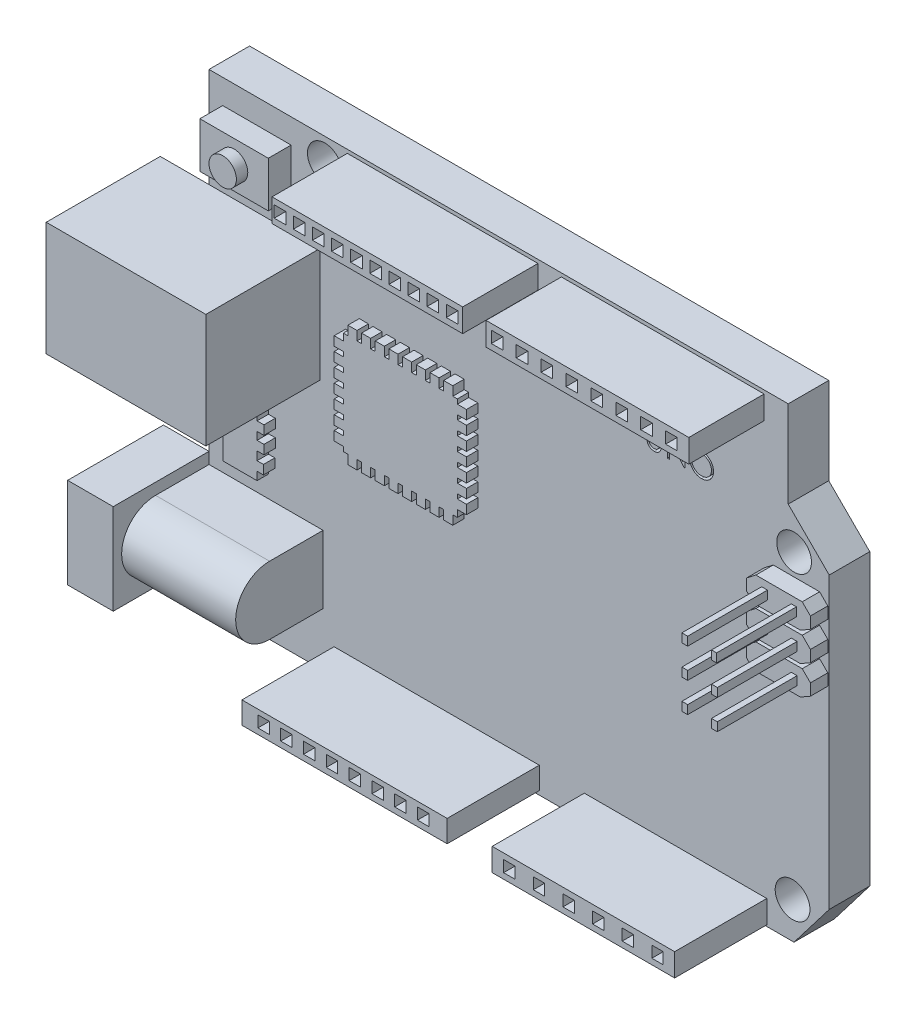
SolidWorks part; units mm, degrees
ref_plane "Front Plane" through (0, 0, 0) normal (0, 0, 1) x (1, 0, 0)
ref_plane "Top Plane" through (0, 0, 0) normal (0, 1, 0) x (1, 0, 0)
ref_plane "Right Plane" through (0, 0, 0) normal (1, 0, 0) x (0, 0, -1)
sketch "Sketch1" plane through (0, 0, 0) normal (0, 0, 1) x (1, 0, 0)
  line L0 (-21.0015, 8.0601) -> (-21.0015, -12.2599)
  line L1 (4.6525, -12.2599) -> (6.197, -10.2435)
  line L2 (6.197, -10.2435) -> (6.197, 2.4565)
  line L4 (4.3985, 8.0601) -> (-21.0015, 8.0601)
  line L5 (-21.0015, -12.2599) -> (4.6525, -12.2599)
  line L6 (6.197, 2.4565) -> (4.3985, 4.2501)
  line L7 (4.3985, 4.2501) -> (4.3985, 8.0601)
  dimension "D1" = 25.654
  dimension "D2" = 20.32
  dimension "D3" = 25.4
  dimension "D4" = 3.81
  dimension "D5" = 2.54
  dimension "D6" = 2.54
  dimension "D7" = 12.7
  dimension "D8" = 27.1985
  dimension "D9" = 20.32
extrude "Boss-Extrude1" add sketch "Sketch1" along normal blind 1.778
sketch "Sketch2" plane through (0, 0, 0) normal (0, 0, 1) x (1, 0, 0)
  line L0 (4.3985, 8.0601) -> (-21.0015, 8.0601) construction
  line L1 (-21.0015, -12.2599) -> (4.6525, -12.2599) construction
  line L2 (-21.0015, 8.0601) -> (-21.0015, -12.2599) construction
  line L3 (6.197, 2.4565) -> (4.3985, 4.2501) construction
  line L4 (4.6525, -12.2599) -> (6.197, -10.2435) construction
  circle A0 centre (4.6572, 2.5572) radius 0.762
  circle A1 centre (-15.9215, 7.0441) radius 0.762
  circle A2 centre (-18.4615, -11.2439) radius 0.762
  circle A3 centre (4.589, -10.6719) radius 0.762
  dimension "D1" = 1.524
  dimension "D2" = 1.524
  dimension "D3" = 1.524
  dimension "D4" = 1.524
  dimension "D10" = 1.016
  dimension "D11" = 1.016
  dimension "D6" = 1.016
  dimension "D7" = 1.016
  dimension "D8" = 5.08
  dimension "D9" = 2.54
extrude "Cut-Extrude6" cut sketch "Sketch2" against normal blind 7.874 and the other way blind 6.35
sketch "Sketch7" plane through (0, 0, 0) normal (0, 0, 1) x (1, 0, 0)
  line L0 (3.8952, 2.5572) -> (3.8952, -2.4896) construction
  line L1 (5.4192, 2.5572) -> (5.4192, -2.4896) construction
  line L2 (5.4192, 2.5572) -> (5.6732, 2.5572) construction
  line L3 (3.8952, 2.5572) -> (3.6412, 2.5572) construction
  line L4 (3.743, 1.6105) -> (5.775, 1.6105)
  line L5 (5.775, 1.6105) -> (6.1342, 1.2512)
  line L6 (6.1342, 1.2512) -> (6.1342, 0.7432)
  line L7 (6.1342, 0.7432) -> (5.6928, 0.4919)
  line L8 (5.6928, 0.4919) -> (3.6412, 0.4919)
  line L9 (3.6412, 0.4919) -> (3.3402, 0.7929)
  line L10 (3.3402, 0.7929) -> (3.3402, 1.3009)
  line L11 (3.3402, 1.3009) -> (3.743, 1.6105)
  line L12 (6.1342, 1.2512) -> (6.1342, -2.4896) construction
  line L13 (6.197, -10.2435) -> (6.197, 2.4565) construction
  line L14 (3.3402, 0.0309) -> (3.743, 0.3405)
  line L15 (3.743, 0.3405) -> (5.775, 0.3405)
  line L16 (5.775, 0.3405) -> (6.1342, -0.0188)
  line L17 (6.1342, -0.0188) -> (6.1342, -0.5268)
  line L18 (6.1342, -0.5268) -> (5.6928, -0.7781)
  line L19 (5.6928, -0.7781) -> (3.6412, -0.7781)
  line L20 (3.6412, -0.7781) -> (3.3402, -0.4771)
  line L21 (3.3402, -0.4771) -> (3.3402, 0.0309)
  line L22 (3.3402, -1.2391) -> (3.743, -0.9295)
  line L23 (3.743, -0.9295) -> (5.775, -0.9295)
  line L24 (5.775, -0.9295) -> (6.1342, -1.2888)
  line L25 (6.1342, -1.2888) -> (6.1342, -1.7968)
  line L26 (6.1342, -1.7968) -> (5.6928, -2.0481)
  line L27 (5.6928, -2.0481) -> (3.6412, -2.0481)
  line L28 (3.6412, -2.0481) -> (3.3402, -1.7471)
  line L29 (3.3402, -1.7471) -> (3.3402, -1.2391)
  circle A0 centre (4.6572, 2.5572) radius 0.762 construction
  dimension "D1" = 0.254
  dimension "D2" = 0.254
  dimension "D3" = 0.508
  dimension "D4" = 0.508
  dimension "D5" = 0.4257
  dimension "D6" = 0.508
  dimension "D7" = 0.508
  dimension "D8" = 0.508
  dimension "D9" = 0.0628
  dimension "D11" = 1.1185
  dimension "D10" = 3
extrude "Boss-Extrude5" add sketch "Sketch7" along normal blind 2.54
sketch "Sketch8" plane through (0, 0, 0) normal (0, 0, 1) x (1, 0, 0)
  line L0 (1.2329, 7.6506) -> (1.2329, 7.1426)
  line L1 (3.3411, 7.9046) -> (-5.5489, 7.9046)
  line L2 (3.3411, 7.9046) -> (3.3411, 6.8886)
  line L3 (3.3411, 6.8886) -> (-5.5489, 6.8886)
  line L4 (-5.5489, 7.9046) -> (-5.5489, 6.8886)
  line L5 (2.3251, 7.6506) -> (2.8331, 7.6506)
  line L6 (2.3251, 7.6506) -> (2.3251, 7.1426)
  line L7 (2.3251, 7.1426) -> (2.8331, 7.1426)
  line L8 (2.8331, 7.6506) -> (2.8331, 7.1426)
  line L9 (1.2329, 7.6506) -> (1.7409, 7.6506)
  line L10 (1.7409, 7.6506) -> (1.7409, 7.1426)
  line L11 (1.2329, 7.1426) -> (1.7409, 7.1426)
  line L12 (0.1407, 7.6506) -> (0.1407, 7.1426)
  line L13 (0.1407, 7.6506) -> (0.6487, 7.6506)
  line L14 (0.6487, 7.6506) -> (0.6487, 7.1426)
  line L15 (0.1407, 7.1426) -> (0.6487, 7.1426)
  line L16 (-0.9515, 7.6506) -> (-0.9515, 7.1426)
  line L17 (-0.9515, 7.6506) -> (-0.4435, 7.6506)
  line L18 (-0.4435, 7.6506) -> (-0.4435, 7.1426)
  line L19 (-0.9515, 7.1426) -> (-0.4435, 7.1426)
  line L20 (-2.0437, 7.6506) -> (-2.0437, 7.1426)
  line L21 (-2.0437, 7.6506) -> (-1.5357, 7.6506)
  line L22 (-1.5357, 7.6506) -> (-1.5357, 7.1426)
  line L23 (-2.0437, 7.1426) -> (-1.5357, 7.1426)
  line L24 (-3.1359, 7.6506) -> (-3.1359, 7.1426)
  line L25 (-3.1359, 7.6506) -> (-2.6279, 7.6506)
  line L26 (-2.6279, 7.6506) -> (-2.6279, 7.1426)
  line L27 (-3.1359, 7.1426) -> (-2.6279, 7.1426)
  line L28 (-4.2281, 7.6506) -> (-4.2281, 7.1426)
  line L29 (-4.2281, 7.6506) -> (-3.7201, 7.6506)
  line L30 (-3.7201, 7.6506) -> (-3.7201, 7.1426)
  line L31 (-4.2281, 7.1426) -> (-3.7201, 7.1426)
  line L32 (-5.3203, 7.6506) -> (-5.3203, 7.1426)
  line L33 (-5.3203, 7.6506) -> (-4.8123, 7.6506)
  line L34 (-4.8123, 7.6506) -> (-4.8123, 7.1426)
  line L35 (-5.3203, 7.1426) -> (-4.8123, 7.1426)
  line L36 (-8.1339, 7.6506) -> (-8.1339, 7.1426)
  line L37 (-6.5746, 7.9046) -> (-14.9348, 7.9046)
  line L38 (-6.5746, 7.9046) -> (-6.5746, 6.8886)
  line L39 (-6.5746, 6.8886) -> (-14.9348, 6.8886)
  line L40 (-14.9348, 7.9046) -> (-14.9348, 6.8886)
  line L41 (-7.2957, 7.6506) -> (-6.7877, 7.6506)
  line L42 (-7.2957, 7.6506) -> (-7.2957, 7.1426)
  line L43 (-7.2957, 7.1426) -> (-6.7877, 7.1426)
  line L44 (-6.7877, 7.6506) -> (-6.7877, 7.1426)
  line L45 (-8.1339, 7.6506) -> (-7.6259, 7.6506)
  line L46 (-7.6259, 7.6506) -> (-7.6259, 7.1426)
  line L47 (-8.1339, 7.1426) -> (-7.6259, 7.1426)
  line L48 (-8.9721, 7.6506) -> (-8.9721, 7.1426)
  line L49 (-8.9721, 7.6506) -> (-8.4641, 7.6506)
  line L50 (-8.4641, 7.6506) -> (-8.4641, 7.1426)
  line L51 (-8.9721, 7.1426) -> (-8.4641, 7.1426)
  line L52 (-9.8103, 7.6506) -> (-9.8103, 7.1426)
  line L53 (-9.8103, 7.6506) -> (-9.3023, 7.6506)
  line L54 (-9.3023, 7.6506) -> (-9.3023, 7.1426)
  line L55 (-9.8103, 7.1426) -> (-9.3023, 7.1426)
  line L56 (-10.6485, 7.6506) -> (-10.6485, 7.1426)
  line L57 (-10.6485, 7.6506) -> (-10.1405, 7.6506)
  line L58 (-10.1405, 7.6506) -> (-10.1405, 7.1426)
  line L59 (-10.6485, 7.1426) -> (-10.1405, 7.1426)
  line L60 (-11.4867, 7.6506) -> (-11.4867, 7.1426)
  line L61 (-11.4867, 7.6506) -> (-10.9787, 7.6506)
  line L62 (-10.9787, 7.6506) -> (-10.9787, 7.1426)
  line L63 (-11.4867, 7.1426) -> (-10.9787, 7.1426)
  line L64 (-12.3249, 7.6506) -> (-12.3249, 7.1426)
  line L65 (-12.3249, 7.6506) -> (-11.8169, 7.6506)
  line L66 (-11.8169, 7.6506) -> (-11.8169, 7.1426)
  line L67 (-12.3249, 7.1426) -> (-11.8169, 7.1426)
  line L68 (-13.1631, 7.6506) -> (-13.1631, 7.1426)
  line L69 (-13.1631, 7.6506) -> (-12.6551, 7.6506)
  line L70 (-12.6551, 7.6506) -> (-12.6551, 7.1426)
  line L71 (-13.1631, 7.1426) -> (-12.6551, 7.1426)
  line L72 (-14.0013, 7.6506) -> (-14.0013, 7.1426)
  line L73 (-14.0013, 7.6506) -> (-13.4933, 7.6506)
  line L74 (-13.4933, 7.6506) -> (-13.4933, 7.1426)
  line L75 (-14.0013, 7.1426) -> (-13.4933, 7.1426)
  line L76 (-14.8395, 7.6506) -> (-14.8395, 7.1426)
  line L77 (-14.8395, 7.6506) -> (-14.3315, 7.6506)
  line L78 (-14.3315, 7.6506) -> (-14.3315, 7.1426)
  line L79 (-14.8395, 7.1426) -> (-14.3315, 7.1426)
  point P4 (3.3411, 7.3966)
  point P9 (2.8331, 7.3966)
  point P46 (-6.7877, 7.3966)
  dimension "D1" = 8.89
  dimension "D2" = 1.016
  dimension "D3" = 0.508
  dimension "D4" = 0.508
  dimension "D5" = 0.508
  dimension "D6" = 7.874
  dimension "D8" = 0.508
  dimension "D9" = 0.508
  dimension "D10" = 0.508
  dimension "D12" = 0.5842
  dimension "D7" = 8
  dimension "D11" = 10
extrude "Boss-Extrude10" add sketch "Sketch8" along normal blind 5.08
sketch "Sketch9" plane through (0, 0, 2.54) normal (0, 0, 1) x (1, 0, 0)
  line L1 (3.997, 1.293) -> (4.251, 1.293)
  line L2 (3.997, 1.293) -> (3.997, 0.912)
  line L3 (3.997, 0.912) -> (4.251, 0.912)
  line L4 (4.251, 1.293) -> (4.251, 0.912)
  line L8 (5.267, 1.293) -> (5.267, 0.912)
  line L9 (5.267, 1.293) -> (5.521, 1.293)
  line L10 (5.521, 1.293) -> (5.521, 0.912)
  line L11 (5.267, 0.912) -> (5.521, 0.912)
  line L12 (5.297, 1.293) -> (5.297, 0.912)
  line L13 (5.297, 1.293) -> (5.551, 1.293)
  line L14 (5.551, 1.293) -> (5.551, 0.912)
  line L15 (5.297, 0.912) -> (5.551, 0.912)
  line L16 (5.297, -0.007) -> (5.297, -0.388)
  line L17 (5.297, -0.007) -> (5.551, -0.007)
  line L18 (5.551, -0.007) -> (5.551, -0.388)
  line L19 (5.297, -0.388) -> (5.551, -0.388)
  line L20 (5.297, -1.307) -> (5.297, -1.688)
  line L21 (5.297, -1.307) -> (5.551, -1.307)
  line L22 (5.551, -1.307) -> (5.551, -1.688)
  line L23 (5.297, -1.688) -> (5.551, -1.688)
  line L24 (3.997, -0.007) -> (3.997, -0.388)
  line L25 (3.997, -0.007) -> (4.251, -0.007)
  line L26 (4.251, -0.007) -> (4.251, -0.388)
  line L27 (3.997, -0.388) -> (4.251, -0.388)
  line L28 (3.997, -1.307) -> (3.997, -1.688)
  line L29 (3.997, -1.307) -> (4.251, -1.307)
  line L30 (4.251, -1.307) -> (4.251, -1.688)
  line L31 (3.997, -1.688) -> (4.251, -1.688)
  point P4 (3.997, 1.1025)
  dimension "D1" = 0.381
  dimension "D2" = 0.254
  dimension "D3" = 0.508
  dimension "D4" = 0.254
  dimension "D6" = 0.254
  dimension "D7" = 2
  dimension "D5" = 2
  dimension "D8" = 3
extrude "Boss-Extrude14" add sketch "Sketch9" along normal blind 3.5 contours L4 L1 L2 L3 | L9 L12 L11 L10 | L16 L19 L18 L17 | L24 L27 L26 L25 | L20 L23 L22 L21 | L28 L31 L30 L29
sketch "Sketch10" plane through (0, 0, 1.778) normal (0, 0, 1) x (1, 0, 0)
  line L1 (-20.4015, 6.9869) -> (-17.4015, 6.9869)
  line L2 (-20.4015, 6.9869) -> (-20.4015, 4.9869)
  line L3 (-20.4015, 4.9869) -> (-17.4015, 4.9869)
  line L4 (-17.4015, 6.9869) -> (-17.4015, 4.9869)
  dimension "D1" = 2
  dimension "D2" = 3
  dimension "D3" = 0.6
extrude "Boss-Extrude15" add sketch "Sketch10" along normal blind 1
sketch "Sketch11" plane through (0, 0, 2.778) normal (0, 0, 1) x (1, 0, 0)
  line L0 (-20.4015, 6.9869) -> (-20.4015, 4.9869) construction
  line L1 (-17.4015, 6.9869) -> (-20.4015, 6.9869) construction
  circle A0 centre (-18.9015, 5.9869) radius 0.6
  point P0 (-20.4015, 5.9869)
  point P1 (-18.9015, 6.9869)
  point P10 (-18.9015, 5.9869)
  dimension "D1" = 1.2
extrude "Boss-Extrude16" add sketch "Sketch11" along normal blind 0.5
sketch "Sketch21" plane through (0, 0, 1.778) normal (0, 0, 1) x (1, 0, 0)
  line L1 (-23.14, 3.687) -> (-16.14, 3.687)
  line L2 (-23.14, 3.687) -> (-23.14, -1.313)
  line L3 (-23.14, -1.313) -> (-16.14, -1.313)
  line L4 (-16.14, 3.687) -> (-16.14, -1.313)
  dimension "D1" = 7
  dimension "D2" = 5
extrude "Boss-Extrude20" add sketch "Sketch21" along normal blind 5 contours L2 L1 L4 L3
sketch "Sketch22" plane through (-23.14, 0, 0) normal (-1, 0, 0) x (0, 0, 1)
  line L0 (5.4441, 2.1094) -> (5.4441, 0.2551)
  line L1 (5.4441, 0.2551) -> (4.6306, -0.5583)
  line L2 (4.6306, -0.5583) -> (3.1119, -0.5583)
  line L3 (3.1119, -0.5583) -> (3.1119, 2.9417)
  line L4 (3.1119, 2.9417) -> (4.6119, 2.9417)
  line L5 (4.6119, 2.9417) -> (5.4441, 2.1094)
  line L6 (5.4441, 1.1823) -> (3.1119, 1.1917) construction
  line L7 (4.278, 1.187) -> (4.278, -0.5583) construction
  point P11 (4.278, 1.187)
  dimension "D1" = 45
  dimension "D2" = 45
  dimension "D3" = 1.5
  dimension "D4" = 3.5
  dimension "D5" = 2.5
  dimension "D6" = 2.5
extrude "Cut-Extrude9" cut sketch "Sketch22" against normal blind 6
sketch "Sketch23" plane through (-17.14, 0, 0) normal (-1, 0, 0) x (0, 0, 1)
  line L0 (4.8177, 1.1917) -> (3.906, 1.1917) construction
  line L1 (4.5825, 1.7725) -> (3.906, 1.7725)
  line L2 (4.5825, 1.7725) -> (4.5825, 0.6108)
  line L3 (4.5825, 0.6108) -> (3.906, 0.6108)
  line L4 (3.906, 1.7725) -> (3.906, 0.6108)
  line L5 (4.2443, 1.7725) -> (4.2443, 0.6108) construction
  line L6 (5.4441, 2.1094) -> (3.1119, 2.1094) construction
  line L7 (3.1119, 2.9417) -> (3.1119, -0.5583) construction
  point P5 (4.3619, 1.1917)
  dimension "D1" = 1.75
  dimension "D2" = 2.3322
  dimension "D3" = 1.25
  dimension "D4" = 1.1617
extrude "Boss-Extrude21" add sketch "Sketch23" along normal blind 6
sketch "Sketch25" plane through (0, 0, 1.778) normal (0, 0, 1) x (1, 0, 0)
  line L1 (-19.8949, -3.5053) -> (-18.3949, -3.5053)
  line L2 (-19.8949, -3.5053) -> (-19.8949, -6.0053)
  line L3 (-19.8949, -6.0053) -> (-18.3949, -6.0053)
  line L4 (-18.3949, -3.5053) -> (-18.3949, -3.7342)
  line L8 (-18.3949, -4.1342) -> (-18.3949, -4.4734)
  line L9 (-18.3949, -3.7342) -> (-18.0942, -3.7342)
  line L10 (-18.3949, -4.1342) -> (-18.0942, -4.1342)
  line L11 (-18.0942, -3.7342) -> (-18.0942, -4.1342)
  line L12 (-18.3949, -4.8734) -> (-18.3949, -5.2482)
  line L13 (-18.3949, -4.4734) -> (-18.0916, -4.4734)
  line L14 (-18.3949, -4.8734) -> (-18.0916, -4.8734)
  line L15 (-18.0916, -4.4734) -> (-18.0916, -4.8734)
  line L16 (-18.3949, -5.6482) -> (-18.3949, -6.0053)
  line L17 (-18.3949, -5.2482) -> (-18.1145, -5.2482)
  line L18 (-18.3949, -5.6482) -> (-18.1145, -5.6482)
  line L19 (-18.1145, -5.2482) -> (-18.1145, -5.6482)
  dimension "D1" = 2.5
  dimension "D2" = 1.5
  dimension "D3" = 0.3571
  dimension "D4" = 0.3748
  dimension "D6" = 0.4
  dimension "D7" = 0.4
  dimension "D8" = 0.4
extrude "Boss-Extrude22" add sketch "Sketch25" along normal blind 0.5
ref_plane "Plane2" through (0, 0, 0) normal (1, 0, 0) x (0, 0, -1)
sketch "Sketch30" plane through (0, 0, 0) normal (1, 0, 0) x (0, 0, -1)
  line L0 (-4.1243, -6.9435) -> (-1.6243, -6.9435)
  line L1 (-1.6243, -6.9435) -> (-1.6243, -9.9172)
  line L2 (-1.6243, -9.9172) -> (-4.1243, -9.9172)
  arc A0 (-4.1243, -9.9172) -> (-4.1243, -6.9435) centre (-4.1243, -8.4303) cw
  dimension "D1" = 2.5
extrude "Boss-Extrude25" add sketch "Sketch30" against normal blind 21 and the other way blind 1
sketch "Sketch31" plane through (1, 0, 0) normal (1, 0, 0) x (0, 0, -1)
  line L0 (-4.1243, -9.9172) -> (-1.778, -9.9172)
  line L1 (-1.778, -9.9172) -> (-1.778, -6.9435)
  line L2 (-1.778, -6.9435) -> (-4.1243, -6.9435)
  arc A0 (-4.1243, -9.9172) -> (-4.1243, -6.9435) centre (-4.1243, -8.4303) cw
  arc A1 (-4.1243, -6.9435) -> (-4.1243, -9.9172) centre (-4.1243, -8.4303) ccw construction
extrude "Cut-Extrude10" cut sketch "Sketch31" against normal blind 17
sketch "Sketch32" plane through (-21, 0, 0) normal (-1, 0, 0) x (0, 0, 1)
  line L1 (1.7793, -6.4435) -> (5.9793, -6.4435)
  line L2 (1.7793, -6.4435) -> (1.7793, -10.4172)
  line L3 (1.7793, -10.4172) -> (5.9793, -10.4172)
  line L4 (5.9793, -6.4435) -> (5.9793, -10.4172)
  dimension "D1" = 0.5
  dimension "D2" = 0.5
  dimension "D3" = 4.2
extrude "Boss-Extrude26" add sketch "Sketch32" along normal blind 2
sketch "Sketch33" plane through (-23, 0, 0) normal (-1, 0, 0) x (0, 0, 1)
  line L0 (5.9793, -8.4303) -> (1.7793, -8.4303) construction
  line L1 (5.9793, -10.4172) -> (5.9793, -6.4435) construction
  line L2 (1.7793, -6.4435) -> (1.7793, -10.4172) construction
  circle A0 centre (3.8793, -8.4303) radius 1.3
  point P6 (3.8793, -8.4303)
extrude "Cut-Extrude11" cut sketch "Sketch33" against normal blind 2
sketch "Sketch35" plane through (-23, 0, 0) normal (-1, 0, 0) x (0, 0, 1)
  line L0 (5.9793, -8.4303) -> (1.7793, -8.4303) construction
  line L1 (5.9793, -10.4172) -> (5.9793, -6.4435) construction
  line L2 (1.7793, -6.4435) -> (1.7793, -10.4172) construction
  circle A0 centre (3.8793, -8.4303) radius 0.2
  point P6 (3.8793, -8.4303)
  dimension "D1" = 0.4
extrude "Boss-Extrude27" add sketch "Sketch35" along normal blind 0.04 and the other way blind 2 contours A0
sketch "Sketch36" plane through (0, 0, 1.778) normal (0, 0, 1) x (1, 0, 0)
  line L0 (1.1581, -11.4468) -> (1.1581, -11.9468)
  line L1 (3.4581, -12.1968) -> (-4.5419, -12.1968)
  line L2 (3.4581, -12.1968) -> (3.4581, -11.1968)
  line L3 (3.4581, -11.1968) -> (-4.5419, -11.1968)
  line L4 (-4.5419, -12.1968) -> (-4.5419, -11.1968)
  line L5 (2.4581, -11.4468) -> (2.9581, -11.4468)
  line L6 (2.4581, -11.4468) -> (2.4581, -11.9468)
  line L7 (2.4581, -11.9468) -> (2.9581, -11.9468)
  line L8 (2.9581, -11.4468) -> (2.9581, -11.9468)
  line L9 (1.1581, -11.4468) -> (1.6581, -11.4468)
  line L10 (1.6581, -11.4468) -> (1.6581, -11.9468)
  line L11 (1.1581, -11.9468) -> (1.6581, -11.9468)
  line L12 (-0.1419, -11.4468) -> (-0.1419, -11.9468)
  line L13 (-0.1419, -11.4468) -> (0.3581, -11.4468)
  line L14 (0.3581, -11.4468) -> (0.3581, -11.9468)
  line L15 (-0.1419, -11.9468) -> (0.3581, -11.9468)
  line L16 (-1.4419, -11.4468) -> (-1.4419, -11.9468)
  line L17 (-1.4419, -11.4468) -> (-0.9419, -11.4468)
  line L18 (-0.9419, -11.4468) -> (-0.9419, -11.9468)
  line L19 (-1.4419, -11.9468) -> (-0.9419, -11.9468)
  line L20 (-2.7419, -11.4468) -> (-2.7419, -11.9468)
  line L21 (-2.7419, -11.4468) -> (-2.2419, -11.4468)
  line L22 (-2.2419, -11.4468) -> (-2.2419, -11.9468)
  line L23 (-2.7419, -11.9468) -> (-2.2419, -11.9468)
  line L24 (-4.0419, -11.4468) -> (-4.0419, -11.9468)
  line L25 (-4.0419, -11.4468) -> (-3.5419, -11.4468)
  line L26 (-3.5419, -11.4468) -> (-3.5419, -11.9468)
  line L27 (-4.0419, -11.9468) -> (-3.5419, -11.9468)
  point P8 (2.9581, -11.6968)
  dimension "D1" = 1
  dimension "D2" = 8
  dimension "D3" = 0.5
  dimension "D4" = 0.5
  dimension "D5" = 0.5
  dimension "D6" = 0.5
extrude "Boss-Extrude28" add sketch "Sketch36" along normal blind 4.04
sketch "Sketch39" plane through (0, 0, 1.778) normal (0, 0, 1) x (1, 0, 0)
  line L0 (-8.8176, -11.3377) -> (-8.8176, -11.8377)
  line L1 (-6.5176, -12.0877) -> (-15.5176, -12.0877)
  line L2 (-6.5176, -12.0877) -> (-6.5176, -11.1226)
  line L3 (-6.5176, -11.1226) -> (-15.5176, -11.1226)
  line L4 (-15.5176, -12.0877) -> (-15.5176, -11.1226)
  line L5 (-7.8176, -11.3377) -> (-7.3176, -11.3377)
  line L6 (-7.8176, -11.3377) -> (-7.8176, -11.8377)
  line L7 (-7.8176, -11.8377) -> (-7.3176, -11.8377)
  line L8 (-7.3176, -11.3377) -> (-7.3176, -11.8377)
  line L9 (-8.8176, -11.3377) -> (-8.3176, -11.3377)
  line L10 (-8.3176, -11.3377) -> (-8.3176, -11.8377)
  line L11 (-8.8176, -11.8377) -> (-8.3176, -11.8377)
  line L12 (-9.8176, -11.3377) -> (-9.8176, -11.8377)
  line L13 (-9.8176, -11.3377) -> (-9.3176, -11.3377)
  line L14 (-9.3176, -11.3377) -> (-9.3176, -11.8377)
  line L15 (-9.8176, -11.8377) -> (-9.3176, -11.8377)
  line L16 (-10.8176, -11.3377) -> (-10.8176, -11.8377)
  line L17 (-10.8176, -11.3377) -> (-10.3176, -11.3377)
  line L18 (-10.3176, -11.3377) -> (-10.3176, -11.8377)
  line L19 (-10.8176, -11.8377) -> (-10.3176, -11.8377)
  line L20 (-11.8176, -11.3377) -> (-11.8176, -11.8377)
  line L21 (-11.8176, -11.3377) -> (-11.3176, -11.3377)
  line L22 (-11.3176, -11.3377) -> (-11.3176, -11.8377)
  line L23 (-11.8176, -11.8377) -> (-11.3176, -11.8377)
  line L24 (-12.8176, -11.3377) -> (-12.8176, -11.8377)
  line L25 (-12.8176, -11.3377) -> (-12.3176, -11.3377)
  line L26 (-12.3176, -11.3377) -> (-12.3176, -11.8377)
  line L27 (-12.8176, -11.8377) -> (-12.3176, -11.8377)
  line L28 (-13.8176, -11.3377) -> (-13.8176, -11.8377)
  line L29 (-13.8176, -11.3377) -> (-13.3176, -11.3377)
  line L30 (-13.3176, -11.3377) -> (-13.3176, -11.8377)
  line L31 (-13.8176, -11.8377) -> (-13.3176, -11.8377)
  line L32 (-14.8176, -11.3377) -> (-14.8176, -11.8377)
  line L33 (-14.8176, -11.3377) -> (-14.3176, -11.3377)
  line L34 (-14.3176, -11.3377) -> (-14.3176, -11.8377)
  line L35 (-14.8176, -11.8377) -> (-14.3176, -11.8377)
  point P8 (-6.5176, -11.6051)
  point P9 (-7.3176, -11.5877)
  dimension "D1" = 9
  dimension "D2" = 0.9651
  dimension "D3" = 0.5
  dimension "D4" = 0.5
  dimension "D5" = 0.8
  dimension "D6" = 0.5
extrude "Boss-Extrude29" add sketch "Sketch39" along normal blind 4.04
sketch "Sketch40" plane through (0, 0, 1.778) normal (0, 0, 1) x (1, 0, 0)
  text T0 "UNO" font "Century Gothic" height 1
extrude "Cut-Extrude15" cut sketch "Sketch40" against normal blind 0.5
sketch "Sketch42" plane through (0, 0, 1.778) normal (0, 0, 1) x (1, 0, 0)
  line L0 (-9.6124, -1.7091) -> (-9.6124, -1.7048)
  line L1 (-14.6124, 1.4909) -> (-14.4124, 1.4909)
  line L2 (-14.6124, 1.4909) -> (-14.6124, 1.1909)
  line L3 (-14.6124, -3.0091) -> (-14.4124, -3.0091)
  line L4 (-9.6124, 1.4909) -> (-9.6124, 1.2909)
  line L5 (-14.6124, -1.8091) -> (-15.0124, -1.8091)
  line L6 (-15.0124, -2.2091) -> (-15.0124, -1.8091)
  line L7 (-14.6124, -2.2091) -> (-15.0124, -2.2091)
  line L24 (-9.6124, -1.6091) -> (-9.6124, -1.7091)
  line L29 (-9.6124, 0.8909) -> (-9.2124, 0.8909)
  line L30 (-9.6124, 1.2909) -> (-9.2124, 1.2909)
  line L31 (-9.2124, 0.8909) -> (-9.2124, 1.2909)
  line L32 (-9.6124, -2.1048) -> (-9.6124, -2.1826)
  line L40 (-9.6124, -2.8091) -> (-9.6124, -3.0091)
  line L44 (-14.6124, -1.2091) -> (-15.0124, -1.2091)
  line L49 (-9.8124, -3.0091) -> (-9.6124, -3.0091)
  line L50 (-9.8124, -3.0091) -> (-9.8124, -3.4091)
  line L51 (-10.2124, -3.0091) -> (-10.2124, -3.4091)
  line L52 (-9.8124, -3.4091) -> (-10.2124, -3.4091)
  line L53 (-10.3124, -3.0091) -> (-10.2124, -3.0091)
  line L69 (-12.2124, -3.0091) -> (-12.0124, -3.0091)
  line L73 (-12.6124, -3.0091) -> (-12.7124, -3.0091)
  line L77 (-13.3124, -3.0091) -> (-13.2124, -3.0091)
  line L85 (-14.6124, -2.8091) -> (-14.6124, -3.0091)
  line L86 (-14.6124, -2.8091) -> (-15.0124, -2.8091)
  line L87 (-14.6124, -2.4091) -> (-15.0124, -2.4091)
  line L88 (-15.0124, -2.8091) -> (-15.0124, -2.4091)
  line L89 (-15.0124, -1.6091) -> (-15.0124, -1.2091)
  line L90 (-14.6124, -1.6091) -> (-15.0124, -1.6091)
  line L91 (-14.6124, -0.6091) -> (-15.0124, -0.6091)
  line L92 (-15.0124, -1.0091) -> (-15.0124, -0.6091)
  line L93 (-14.6124, -1.0091) -> (-15.0124, -1.0091)
  line L94 (-14.6124, -0.0091) -> (-15.0124, -0.0091)
  line L95 (-15.0124, -0.4091) -> (-15.0124, -0.0091)
  line L96 (-14.6124, -0.4091) -> (-15.0124, -0.4091)
  line L97 (-14.6124, 0.5909) -> (-15.0124, 0.5909)
  line L98 (-15.0124, 0.1909) -> (-15.0124, 0.5909)
  line L99 (-14.6124, 0.1909) -> (-15.0124, 0.1909)
  line L100 (-14.6124, 1.1909) -> (-15.0124, 1.1909)
  line L101 (-15.0124, 0.7909) -> (-15.0124, 1.1909)
  line L102 (-14.6124, 0.7909) -> (-15.0124, 0.7909)
  line L103 (-13.4124, 1.4909) -> (-13.4124, 1.8909)
  line L104 (-13.8124, 1.8909) -> (-13.4124, 1.8909)
  line L105 (-13.8124, 1.4909) -> (-13.8124, 1.8909)
  line L106 (-12.8124, 1.4909) -> (-12.8124, 1.8909)
  line L107 (-14.0124, 1.4909) -> (-13.8124, 1.4909)
  line L108 (-14.4124, 1.4909) -> (-14.4124, 1.8909)
  line L109 (-14.0124, 1.4909) -> (-14.0124, 1.8909)
  line L110 (-14.4124, 1.8909) -> (-14.0124, 1.8909)
  line L111 (-13.2124, 1.8909) -> (-12.8124, 1.8909)
  line L112 (-13.2124, 1.4909) -> (-13.2124, 1.8909)
  line L113 (-12.2124, 1.4909) -> (-12.2124, 1.8909)
  line L114 (-12.6124, 1.8909) -> (-12.2124, 1.8909)
  line L115 (-12.6124, 1.4909) -> (-12.6124, 1.8909)
  line L116 (-11.6124, 1.4909) -> (-11.6124, 1.8909)
  line L117 (-12.0124, 1.8909) -> (-11.6124, 1.8909)
  line L118 (-12.0124, 1.4909) -> (-12.0124, 1.8909)
  line L119 (-11.0124, 1.4909) -> (-11.0124, 1.8909)
  line L120 (-11.4124, 1.8909) -> (-11.0124, 1.8909)
  line L121 (-11.4124, 1.4909) -> (-11.4124, 1.8909)
  line L122 (-10.4124, 1.4909) -> (-10.4124, 1.8909)
  line L123 (-10.8124, 1.8909) -> (-10.4124, 1.8909)
  line L124 (-10.8124, 1.4909) -> (-10.8124, 1.8909)
  line L125 (-9.8124, 1.4909) -> (-9.8124, 1.8909)
  line L126 (-10.2124, 1.8909) -> (-9.8124, 1.8909)
  line L127 (-10.2124, 1.4909) -> (-10.2124, 1.8909)
  line L128 (-14.0124, -3.0091) -> (-13.8124, -3.0091)
  line L129 (-10.8124, -3.0091) -> (-10.8124, -3.4091)
  line L130 (-10.4124, -3.4091) -> (-10.8124, -3.4091)
  line L131 (-10.4124, -3.0091) -> (-10.4124, -3.4091)
  line L132 (-11.4124, -3.0091) -> (-11.4124, -3.4091)
  line L133 (-11.0124, -3.4091) -> (-11.4124, -3.4091)
  line L134 (-11.0124, -3.0091) -> (-11.0124, -3.4091)
  line L135 (-12.0124, -3.0091) -> (-12.0124, -3.4091)
  line L136 (-11.6124, -3.4091) -> (-12.0124, -3.4091)
  line L137 (-11.6124, -3.0091) -> (-11.6124, -3.4091)
  line L138 (-12.6124, -3.0091) -> (-12.6124, -3.4091)
  line L139 (-12.2124, -3.4091) -> (-12.6124, -3.4091)
  line L140 (-12.2124, -3.0091) -> (-12.2124, -3.4091)
  line L141 (-13.2124, -3.0091) -> (-13.2124, -3.4091)
  line L142 (-12.8124, -3.4091) -> (-13.2124, -3.4091)
  line L143 (-12.8124, -3.0091) -> (-12.8124, -3.4091)
  line L144 (-13.8124, -3.0091) -> (-13.8124, -3.4091)
  line L145 (-13.4124, -3.4091) -> (-13.8124, -3.4091)
  line L146 (-13.4124, -3.0091) -> (-13.4124, -3.4091)
  line L147 (-14.4124, -3.0091) -> (-14.4124, -3.4091)
  line L148 (-14.0124, -3.4091) -> (-14.4124, -3.4091)
  line L149 (-14.0124, -3.0091) -> (-14.0124, -3.4091)
  line L150 (-9.6124, -2.8091) -> (-9.6124, -2.7091)
  line L151 (-9.6124, 0.6909) -> (-9.2124, 0.6909)
  line L152 (-9.2124, 0.2909) -> (-9.2124, 0.6909)
  line L153 (-9.6124, 0.2909) -> (-9.2124, 0.2909)
  line L154 (-9.6124, 0.0909) -> (-9.2124, 0.0909)
  line L155 (-9.2124, -0.3091) -> (-9.2124, 0.0909)
  line L156 (-9.6124, -0.3091) -> (-9.2124, -0.3091)
  line L157 (-9.6124, -0.5091) -> (-9.2124, -0.5091)
  line L158 (-9.2124, -0.9091) -> (-9.2124, -0.5091)
  line L159 (-9.6124, -0.9091) -> (-9.2124, -0.9091)
  line L160 (-9.6124, -1.1091) -> (-9.2124, -1.1091)
  line L161 (-9.2124, -1.5091) -> (-9.2124, -1.1091)
  line L162 (-9.6124, -1.5091) -> (-9.2124, -1.5091)
  line L163 (-9.6124, -1.7091) -> (-9.2124, -1.7091)
  line L164 (-9.2124, -2.1091) -> (-9.2124, -1.7091)
  line L165 (-9.6124, -2.1091) -> (-9.2124, -2.1091)
  line L166 (-9.6124, -2.3091) -> (-9.2124, -2.3091)
  line L167 (-9.2124, -2.7091) -> (-9.2124, -2.3091)
  line L168 (-9.6124, -2.7091) -> (-9.2124, -2.7091)
  line L169 (-13.4124, 1.4909) -> (-13.2124, 1.4909)
  line L170 (-12.8124, 1.4909) -> (-12.6124, 1.4909)
  line L171 (-12.2124, 1.4909) -> (-12.0124, 1.4909)
  line L172 (-11.6124, 1.4909) -> (-11.4124, 1.4909)
  line L173 (-11.0124, 1.4909) -> (-10.8124, 1.4909)
  line L174 (-10.4124, 1.4909) -> (-10.2124, 1.4909)
  line L175 (-9.8124, 1.4909) -> (-9.6124, 1.4909)
  line L176 (-9.6124, 0.6909) -> (-9.6124, 0.7909)
  line L177 (-9.6124, 0.8909) -> (-9.6124, 0.7909)
  line L178 (-9.6124, 0.0909) -> (-9.6124, 0.2909)
  line L179 (-9.6124, -0.5091) -> (-9.6124, -0.3091)
  line L180 (-9.6124, -1.1091) -> (-9.6124, -0.9091)
  line L181 (-9.6124, -1.7091) -> (-9.6124, -1.5091)
  line L182 (-9.6124, -2.3091) -> (-9.6124, -2.1048)
  line L183 (-10.4124, -3.0091) -> (-10.2124, -3.0091)
  line L184 (-11.0124, -3.0091) -> (-10.8124, -3.0091)
  line L185 (-12.2124, -3.0091) -> (-12.0124, -3.0091)
  line L186 (-13.4124, -3.0091) -> (-13.2124, -3.0091)
  line L187 (-14.6124, -2.2091) -> (-14.6124, -2.4091)
  line L188 (-14.6124, -1.6091) -> (-14.6124, -1.8091)
  line L189 (-14.6124, -1.0091) -> (-14.6124, -1.2091)
  line L190 (-14.6124, -0.4091) -> (-14.6124, -0.6091)
  line L191 (-14.6124, 0.1909) -> (-14.6124, -0.0091)
  line L192 (-14.6124, 0.7909) -> (-14.6124, 0.5909)
  line L193 (-12.8124, -3.0091) -> (-12.6124, -3.0091)
  line L194 (-11.6124, -3.0091) -> (-11.4124, -3.0091)
  dimension "D1" = 5
  dimension "D2" = 4.5
  dimension "D21" = 0.2
  dimension "D25" = 0.2
  dimension "D26" = 0.4
  dimension "D27" = 0.4
  dimension "D53" = 0.4
  dimension "D54" = 0.4
  dimension "D55" = 0.2
  dimension "D58" = 0.2
  dimension "D59" = 0.4
  dimension "D60" = 0.4
extrude "Boss-Extrude30" add sketch "Sketch42" along normal blind 0.5
